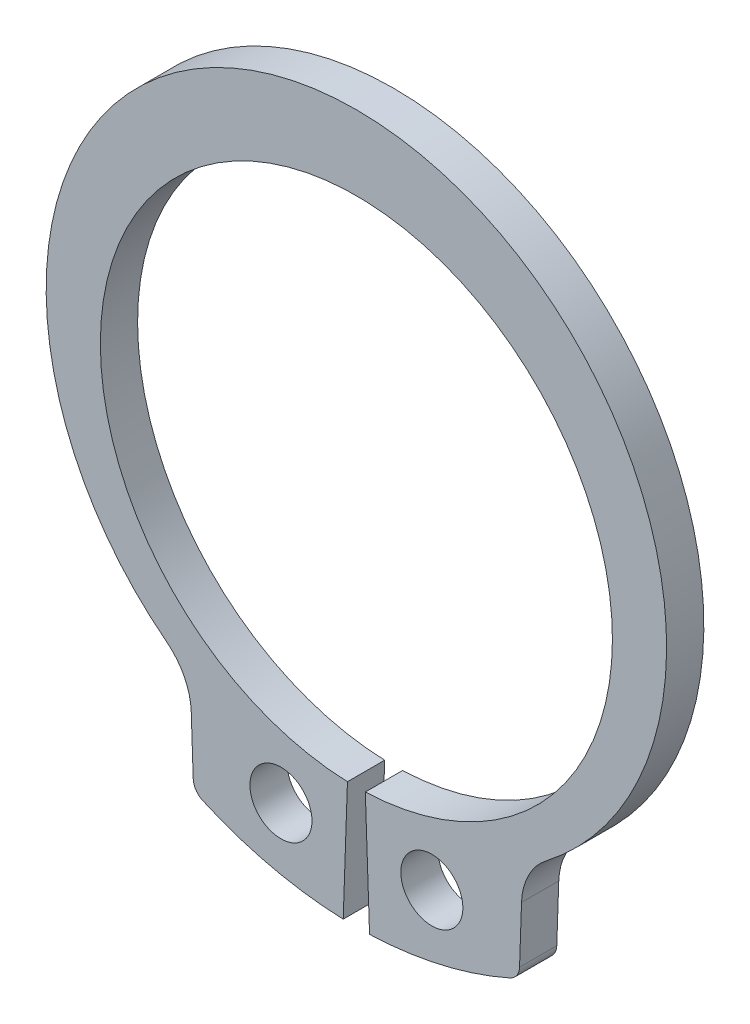
SolidWorks part; units mm, degrees
ref_plane "Front" through (0, 0, 0) normal (0, 0, 1) x (1, 0, 0)
ref_plane "Top" through (0, 0, 0) normal (0, 1, 0) x (1, 0, 0)
ref_plane "Right" through (0, 0, 0) normal (1, 0, 0) x (0, 0, -1)
sketch "Sketch1" plane through (0, 0, 0) normal (0, 0, 1) x (1, 0, 0)
  line L0 (0, 0) -> (-7.1447, -4.125) construction
  line L1 (0, 12.15) -> (0, -12.15) construction
  line L2 (-5.2462, -10.9672) -> (-5.3567, -7.7851) construction
  line L4 (-5.3567, -7.7851) -> (-6.0369, -8.7737) construction
  line L5 (-5.3567, -7.7851) -> (0, 0) construction
  line L6 (0, 8.25) -> (0, 10.65) construction
  line L7 (0, 10.65) -> (0, 9.45) construction
  line L8 (0, -8.25) -> (0, -12.15) construction
  line L9 (-2.8963, -11.8074) -> (0, 0) construction
  line L10 (0, 0) -> (-0.4243, -12.15) construction
  line L11 (-5.2462, -10.9672) -> (0, 0) construction
  line L12 (-5.3244, -8.7155) -> (-6.1186, -7.2502) construction
  line L13 (-5.7215, -7.9828) -> (-5.3567, -7.7851) construction
  line L14 (-1.9654, -8.0125) -> (-2.8963, -11.8074) construction
  line L15 (-2.4308, -9.9099) -> (-1.4596, -10.1482) construction
  arc A0 (0, 10.65) -> (-5.3567, -7.7851) centre (0, 0.6542) ccw construction
  circle A2 centre (0, 0) radius 10.65 construction
  arc A3 (-5.2462, -10.9672) -> (-0.4243, -12.15) centre (0, 0) ccw construction
  circle A4 centre (0, 0) radius 8.25 construction
  circle A6 centre (-2.4308, -9.9099) radius 1 construction
  arc A7 (-6.1186, -7.2502) -> (-5.3244, -8.7155) centre (-7.3826, -8.8832) cw construction
  circle A9 centre (0, 0) radius 9 construction
  circle A10 centre (0, 0) radius 8.5 construction
  point P5 (-7.1447, -4.125)
  point P24 (-4.5957, -9.6074)
  point P35 (0, 10.65)
  point P36 (0, 8.25)
  point P37 (0, -8.25)
  point P38 (0, -12.15)
  dimension "Hole Diameter" = 2
  dimension "D10" = 2.0651
  dimension "For OD" = 18
  dimension "ID" = 16.5
  dimension "Max Sec." = 2.4
  dimension "Lug Height" = 3.9
  dimension "D6" = 2
  dimension "D5" = 3.184
  dimension "D8" = 1.6667
  dimension "D3" = 120
  dimension "D2" = 5
  dimension "D4" = 1.6667
sketch "Sketch2" plane through (0, 0, 0) normal (-1, 0, 0) x (0, 1, 0)
  line L0 (-10.65, 0.6) -> (-10.65, -0.6) construction
  line L1 (10.65, -0.65) -> (10.65, 0.65) construction
  line L2 (0, 0.6) -> (0, -0.6) construction
  line L4 (-10.65, 0) -> (10.65, 0) construction
  point P3 (-10.65, 0)
  point P6 (0, 0)
  point P14 (10.65, 0)
  dimension "Thickness" = 1.2
  dimension "For Groove Width" = 1.3
sketch "Sketch4" plane through (0, 0, 0) normal (0, 0, 1) x (1, 0, 0)
  line L0 (-5.2462, -10.9672) -> (-5.3567, -7.7851) construction
  line L1 (-5.2462, -10.9672) -> (-5.3567, -7.7851)
  line L2 (0, 10.65) -> (0, 8.25)
  line L3 (-0.4243, -12.15) -> (-0.2879, -8.245)
  line L4 (0, 0) -> (-0.4243, -12.15) construction
  arc A0 (0, 10.65) -> (-5.3567, -7.7851) centre (0, 0.6542) ccw construction
  arc A1 (-5.2462, -10.9672) -> (-0.4243, -12.15) centre (0, 0) ccw construction
  circle A2 centre (-2.4308, -9.9099) radius 1 construction
  arc A4 (0, 10.65) -> (-5.3567, -7.7851) centre (0, 0.6542) ccw
  arc A5 (-5.2462, -10.9672) -> (-0.4243, -12.15) centre (0, 0) ccw
  circle A6 centre (-2.4308, -9.9099) radius 1
  circle A7 centre (0, 0) radius 8.25 construction
  arc A8 (0, 8.25) -> (-0.2879, -8.245) centre (0, 0) ccw
extrude "Boss-Extrude1" add sketch "Sketch4" along normal mid plane 1.2
fillet "Fillet1" radius 2.0651 1 edges at (-5.3567, -7.7851, 0)
fillet "Fillet2" radius 0.5163 1 edges at (-5.2462, -10.9672, 0)
mirror "Mirror1" about plane through (0, 10.65, 0.6) normal (-1, 0, 0) of bodies 109
sketch "Sketch3" plane through (0, 0, 0.6) normal (0, 0, 1) x (1, 0, 0)
  line L0 (5.3622, -6.2697) -> (6.1205, -7.2487) construction
  line L1 (6.1205, -7.2487) -> (7.0995, -6.4905) construction
  line L2 (0, 10.65) -> (0, 8.25) construction
  circle A0 centre (0, 0) radius 8.25 construction
  arc A1 (6.1205, -7.2487) -> (-6.1205, -7.2487) centre (0, 0.6542) ccw construction
equation "\"D1@Fillet1\" = \"D10@Sketch1\""
equation "\"D1@Fillet2\" = \"D10@Sketch1\" / 4"
equation "\"Thickness@Boss-Extrude1\"  = \"Ring Thickness@Sketch5\""
equation "\"D2@Sketch1\"=\"Hole Diameter@Sketch1\"*2.5"
equation "\"D4@Sketch1\"=\"D2@Sketch1\"/3"
equation "\"D8@Sketch1\"=\"D4@Sketch1\""
